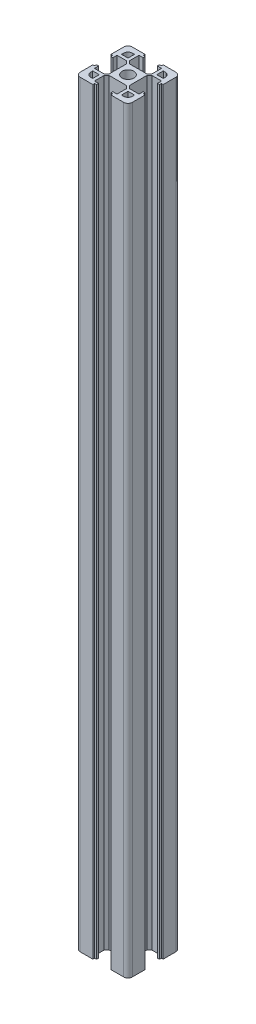
SolidWorks part; units mm, degrees
material "氧化铝"
ref_plane "前视基准面" through (0, 0, 0) normal (0, 0, 1) x (1, 0, 0)
ref_plane "上视基准面" through (0, 0, 0) normal (0, 1, 0) x (1, 0, 0)
ref_plane "右视基准面" through (0, 0, 0) normal (1, 0, 0) x (0, 0, -1)
sketch "草图1" plane through (0, 0, 0) normal (0, 1, 0) x (1, 0, 0)
  line L0 (-1000, 0) -> (49000, 0) construction
  line L1 (0, -1000) -> (0, 49000) construction
  line L2 (-12.8, 4.1) -> (-12.8, 6.4956)
  line L3 (-12.8, 6.4956) -> (-7.2734, 6.4956)
  line L4 (-7.2734, 6.4956) -> (-5.8, 5.0222)
  line L5 (-5.8, 5.0222) -> (-5.8, 0)
  line L6 (-12.8, 4.1) -> (-14, 4.1)
  line L7 (-14, 4.1) -> (-14, 5.2)
  line L8 (-14, 5.2) -> (-15, 5.2)
  line L9 (-15, 5.2) -> (-15, 12.5)
  line L10 (-12, 9.5) -> (-12, 8.25)
  line L11 (-12, 8.25) -> (-8.25, 8.25)
  line L12 (707.1068, -707.1068) -> (-34648.2323, 34648.2323) construction
  line L13 (-8.25, 12) -> (-8.25, 8.25)
  line L14 (-9.5, 12) -> (-8.25, 12)
  line L15 (-5.2, 15) -> (-12.5, 15)
  line L16 (-5.2, 14) -> (-5.2, 15)
  line L17 (-4.1, 14) -> (-5.2, 14)
  line L18 (-4.1, 12.8) -> (-4.1, 14)
  line L19 (-5.0222, 5.8) -> (0, 5.8)
  line L20 (-6.4956, 7.2734) -> (-5.0222, 5.8)
  line L21 (-6.4956, 12.8) -> (-6.4956, 7.2734)
  line L22 (-4.1, 12.8) -> (-6.4956, 12.8)
  line L23 (4.1, 12.8) -> (6.4956, 12.8)
  line L24 (6.4956, 12.8) -> (6.4956, 7.2734)
  line L25 (6.4956, 7.2734) -> (5.0222, 5.8)
  line L26 (5.0222, 5.8) -> (0, 5.8)
  line L27 (4.1, 12.8) -> (4.1, 14)
  line L28 (4.1, 14) -> (5.2, 14)
  line L29 (5.2, 14) -> (5.2, 15)
  line L30 (5.2, 15) -> (12.5, 15)
  line L31 (9.5, 12) -> (8.25, 12)
  line L32 (8.25, 12) -> (8.25, 8.25)
  line L33 (12, 8.25) -> (8.25, 8.25)
  line L34 (12, 9.5) -> (12, 8.25)
  line L35 (15, 5.2) -> (15, 12.5)
  line L36 (14, 5.2) -> (15, 5.2)
  line L37 (14, 4.1) -> (14, 5.2)
  line L38 (12.8, 4.1) -> (14, 4.1)
  line L39 (5.8, 5.0222) -> (5.8, 0)
  line L40 (7.2734, 6.4956) -> (5.8, 5.0222)
  line L41 (12.8, 6.4956) -> (7.2734, 6.4956)
  line L42 (12.8, 4.1) -> (12.8, 6.4956)
  line L43 (12.8, -4.1) -> (12.8, -6.4956)
  line L44 (12.8, -6.4956) -> (7.2734, -6.4956)
  line L45 (7.2734, -6.4956) -> (5.8, -5.0222)
  line L46 (5.8, -5.0222) -> (5.8, 0)
  line L47 (12.8, -4.1) -> (14, -4.1)
  line L48 (14, -4.1) -> (14, -5.2)
  line L49 (14, -5.2) -> (15, -5.2)
  line L50 (15, -5.2) -> (15, -12.5)
  line L51 (12, -9.5) -> (12, -8.25)
  line L52 (12, -8.25) -> (8.25, -8.25)
  line L53 (8.25, -12) -> (8.25, -8.25)
  line L54 (9.5, -12) -> (8.25, -12)
  line L55 (5.2, -15) -> (12.5, -15)
  line L56 (5.2, -14) -> (5.2, -15)
  line L57 (4.1, -14) -> (5.2, -14)
  line L58 (4.1, -12.8) -> (4.1, -14)
  line L59 (5.0222, -5.8) -> (0, -5.8)
  line L60 (6.4956, -7.2734) -> (5.0222, -5.8)
  line L61 (6.4956, -12.8) -> (6.4956, -7.2734)
  line L62 (4.1, -12.8) -> (6.4956, -12.8)
  line L63 (-4.1, -12.8) -> (-6.4956, -12.8)
  line L64 (-6.4956, -12.8) -> (-6.4956, -7.2734)
  line L65 (-6.4956, -7.2734) -> (-5.0222, -5.8)
  line L66 (-5.0222, -5.8) -> (0, -5.8)
  line L67 (-4.1, -12.8) -> (-4.1, -14)
  line L68 (-4.1, -14) -> (-5.2, -14)
  line L69 (-5.2, -14) -> (-5.2, -15)
  line L70 (-5.2, -15) -> (-12.5, -15)
  line L71 (-9.5, -12) -> (-8.25, -12)
  line L72 (-8.25, -12) -> (-8.25, -8.25)
  line L73 (-12, -8.25) -> (-8.25, -8.25)
  line L74 (-12, -9.5) -> (-12, -8.25)
  line L75 (-15, -5.2) -> (-15, -12.5)
  line L76 (-14, -5.2) -> (-15, -5.2)
  line L77 (-14, -4.1) -> (-14, -5.2)
  line L78 (-12.8, -4.1) -> (-14, -4.1)
  line L79 (-5.8, -5.0222) -> (-5.8, 0)
  line L80 (-7.2734, -6.4956) -> (-5.8, -5.0222)
  line L81 (-12.8, -6.4956) -> (-7.2734, -6.4956)
  line L82 (-12.8, -4.1) -> (-12.8, -6.4956)
  circle A0 centre (0, 0) radius 3.4
  arc A1 (-12, 9.5) -> (-9.5, 12) centre (-9.5, 9.5) cw
  arc A2 (-15, 12.5) -> (-12.5, 15) centre (-12.5, 12.5) cw
  arc A3 (9.5, 12) -> (12, 9.5) centre (9.5, 9.5) cw
  arc A4 (12.5, 15) -> (15, 12.5) centre (12.5, 12.5) cw
  arc A5 (12, -9.5) -> (9.5, -12) centre (9.5, -9.5) cw
  arc A6 (15, -12.5) -> (12.5, -15) centre (12.5, -12.5) cw
  arc A7 (-9.5, -12) -> (-12, -9.5) centre (-9.5, -9.5) cw
  arc A8 (-12.5, -15) -> (-15, -12.5) centre (-12.5, -12.5) cw
  point P32 (-12, 12)
  point P35 (-15, 15)
  point P114 (0, 0)
  dimension "D1" = 6.8
  dimension "D12" = 2.5
  dimension "D2" = 15
  dimension "D3" = 1.1
  dimension "D4" = 9.2
  dimension "D5" = 4.1
  dimension "D6" = 45
  dimension "D7" = 5.2
  dimension "D8" = 1
  dimension "D9" = 2.2
  dimension "D10" = 3.75
  dimension "D11" = 8.25
  dimension "D13" = 4
extrude "凸台-拉伸1" add sketch "草图1" along normal blind 435
